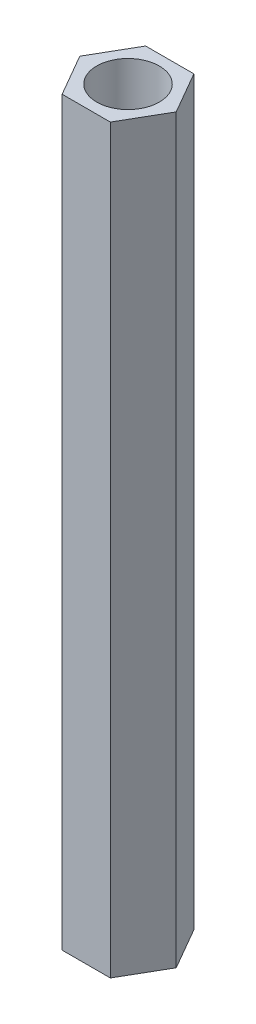
SolidWorks part; units mm, degrees
material "高铅黄铜，UNS C34200"
ref_plane "前视基准面" through (0, 0, 0) normal (0, 0, 1) x (1, 0, 0)
ref_plane "上视基准面" through (0, 0, 0) normal (0, 1, 0) x (1, 0, 0)
ref_plane "右视基准面" through (0, 0, 0) normal (1, 0, 0) x (0, 0, -1)
sketch "草图1" plane through (0, 0, 0) normal (0, 1, 0) x (1, 0, 0)
  line L1 (4.6188, 0) -> (2.3094, 4)
  line L2 (2.3094, 4) -> (-2.3094, 4)
  line L3 (-2.3094, 4) -> (-4.6188, 0)
  line L4 (-4.6188, 0) -> (-2.3094, -4)
  line L5 (-2.3094, -4) -> (2.3094, -4)
  line L6 (2.3094, -4) -> (4.6188, 0)
  circle A0 centre (0, 0) radius 4 construction
  circle A1 centre (0, 0) radius 3
extrude "凸台-拉伸1" add sketch "草图1" along normal blind 71
